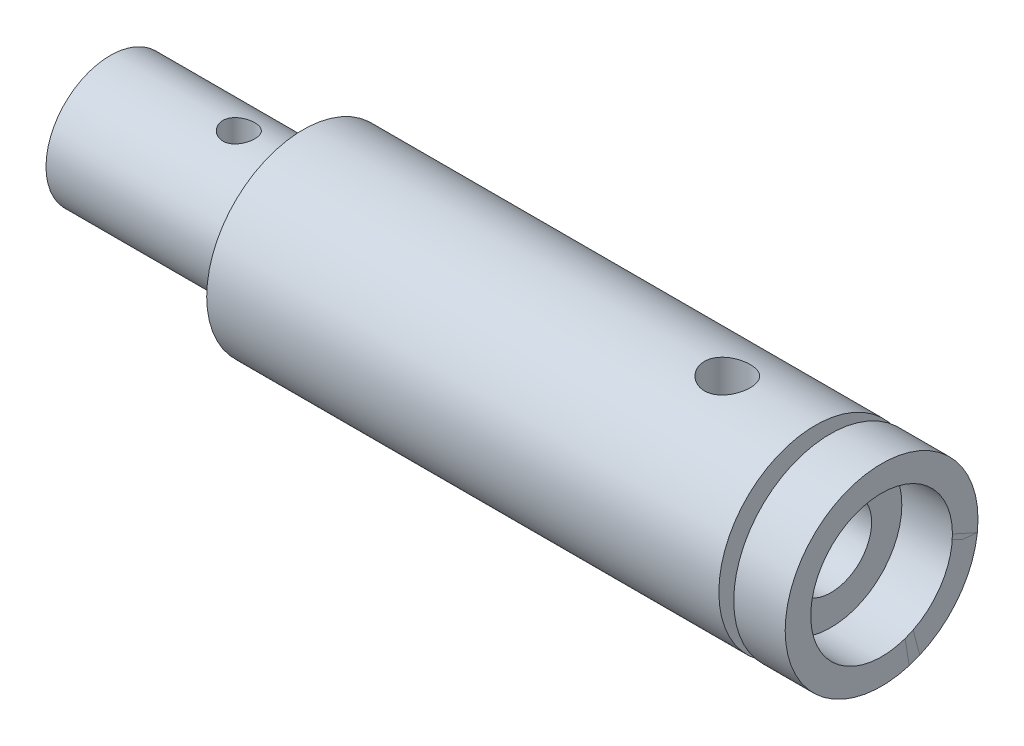
SolidWorks part; units mm, degrees
ref_plane "Front Plane" through (0, 0, 0) normal (0, 0, 1) x (1, 0, 0)
ref_plane "Top Plane" through (0, 0, 0) normal (0, 1, 0) x (1, 0, 0)
ref_plane "Right Plane" through (0, 0, 0) normal (1, 0, 0) x (0, 0, -1)
sketch "Sketch1" plane through (0, 0, 0) normal (1, 0, 0) x (0, 0, -1)
  circle A0 centre (0, 0) radius 4.7625
  dimension "D1" = 9.525
extrude "Boss-Extrude1" add sketch "Sketch1" along normal blind 38.1
sketch "Sketch2" plane through (38.1, 0, 0) normal (1, 0, 0) x (0, 0, -1)
  circle A0 centre (0, 0) radius 2.0066
extrude "Cut-Extrude1" cut sketch "Sketch2" against normal blind 10.414
sketch "Sketch3" plane through (0, 0, 0) normal (0, 1, 0) x (1, 0, 0)
  line L0 (38.1, -4.7625) -> (38.1, 4.7625) construction
  circle A0 centre (30.48, 0) radius 1.1303
  dimension "D1" = 7.62
extrude "Cut-Extrude2" cut sketch "Sketch3" along normal blind 8.6868
sketch "Sketch4" plane through (0, 0, 0) normal (-1, 0, 0) x (0, 0, 1)
  circle A0 centre (0, 0) radius 3.175
  circle A1 centre (0, 0) radius 5.0848
extrude "Cut-Extrude3" cut sketch "Sketch4" against normal blind 9.525
sketch "Sketch5" plane through (0, 0, 0) normal (0, 1, 0) x (1, 0, 0)
  line L0 (9.525, 4.7625) -> (9.525, -4.7625) construction
  circle A0 centre (6.35, 0) radius 0.7874
  dimension "D1" = 3.175
extrude "Cut-Extrude4" cut sketch "Sketch5" against normal through all and the other way through all
sketch "Sketch6" plane through (38.1, 0, 0) normal (1, 0, 0) x (0, 0, -1)
  circle A0 centre (0, 0) radius 3.5
  dimension "D1" = 7
extrude "Cut-Extrude5" cut sketch "Sketch6" against normal blind 2.5 contours A0
surface "Surface-Plane1"
ref_plane "Plane1" through (35.56, 0, 0) normal (1, 0, 0) x (0, 0, -1)
sketch "Sketch7" plane through (35.56, 0, 0) normal (1, 0, 0) x (0, 0, -1)
  circle A0 centre (0, 0) radius 4.7625
  circle A1 centre (0, 0) radius 2.667
  dimension "D1" = 5.334
extrude "Cut-Extrude7" cut sketch "Sketch7" against normal blind 0.7366
